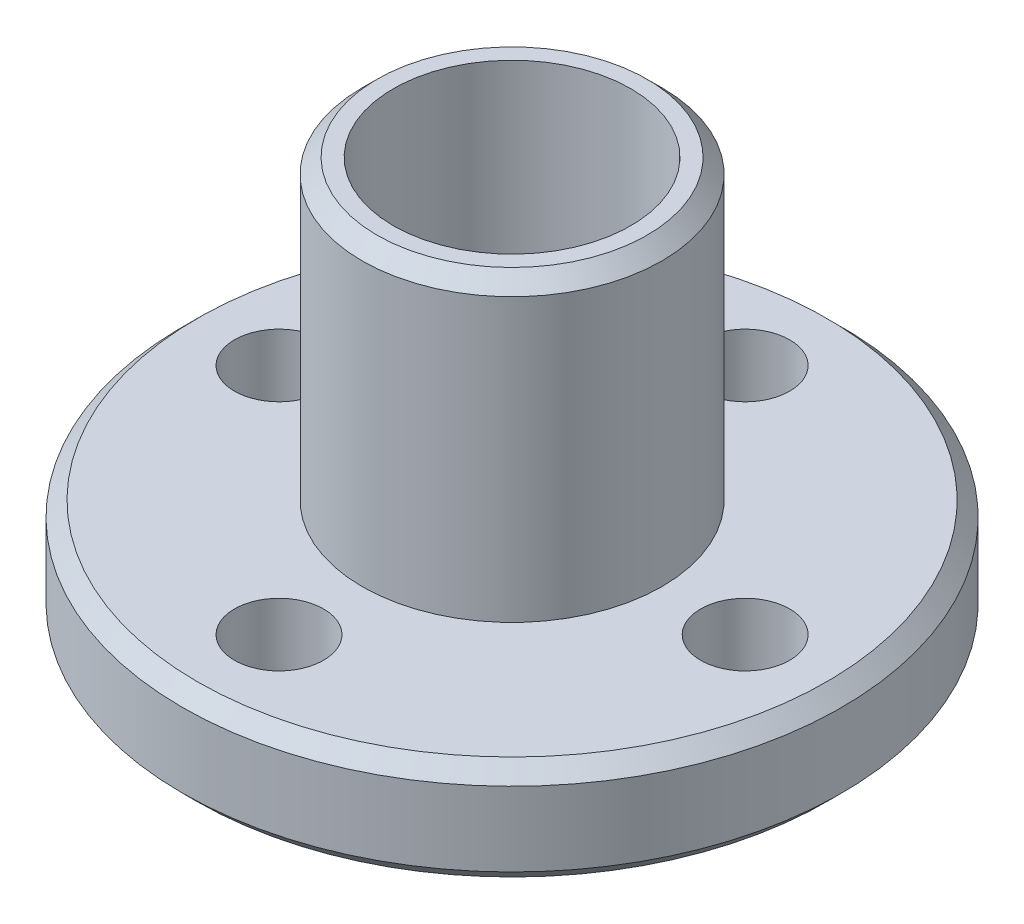
SolidWorks part; units mm, degrees
ref_plane "Front Plane" through (0, 0, 0) normal (0, 0, 1) x (1, 0, 0)
ref_plane "Top Plane" through (0, 0, 0) normal (0, 1, 0) x (1, 0, 0)
ref_plane "Right Plane" through (0, 0, 0) normal (1, 0, 0) x (0, 0, -1)
sketch "Sketch1" plane through (0, 0, 0) normal (0, 1, 0) x (1, 0, 0)
  circle A0 centre (0, 0) radius 11.1
  circle A1 centre (0, 0) radius 4
  dimension "D1" = 22.2
  dimension "D2" = 8
extrude "Boss-Extrude1" add sketch "Sketch1" along normal blind 3.5
sketch "Sketch2" plane through (0, 3.5, 0) normal (0, 1, 0) x (1, 0, 0)
  circle A0 centre (0, 0) radius 4 construction
  circle A1 centre (0, 0) radius 4
  circle A2 centre (0, 0) radius 5.05
extrude "Boss-Extrude2" add sketch "Sketch2" along normal blind 10
sketch "Sketch3" plane through (0, 0, 0) normal (0, -1, 0) x (1, 0, 0)
  circle A0 centre (0, 0) radius 4 construction
  circle A1 centre (0, 0) radius 4
  circle A2 centre (0, 0) radius 5.05
extrude "Boss-Extrude3" add sketch "Sketch3" along normal blind 1.5
sketch "Sketch4" plane through (0, 0, 0) normal (0, -1, 0) x (1, 0, 0)
  line L0 (0, 0) -> (-11.1, 0) construction
  circle A0 centre (0, 0) radius 11.1 construction
  circle A1 centre (-7.85, 0) radius 1.5
  circle A2 centre (0, 7.85) radius 1.5
  circle A3 centre (7.85, 0) radius 1.5
  circle A4 centre (0, -7.85) radius 1.5
  point P17 (0, 0)
  dimension "D1" = 3
  dimension "D3" = 4
  dimension "D2" = 7.85
extrude "Cut-Extrude1" cut sketch "Sketch4" against normal up to next
chamfer "Chamfer1" distance 0.5 angle 45 4 edges at (0, 13.5, 5.05) (0, 3.5, 11.1) (0, 0, 11.1) (0, -1.5, -5.05)
chamfer "Chamfer2" distance 0.5 angle 45 1 edges at (0, 0, 5.05)
